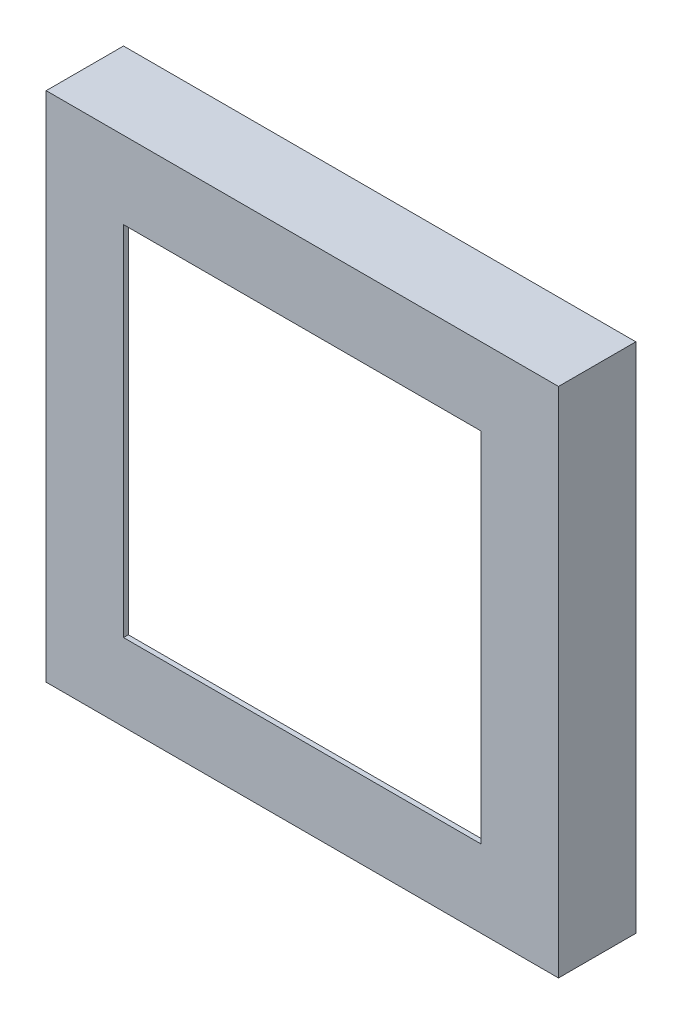
SolidWorks part; units mm, degrees
ref_plane "Front Plane" through (0, 0, 0) normal (0, 0, 1) x (1, 0, 0)
ref_plane "Top Plane" through (0, 0, 0) normal (0, 1, 0) x (1, 0, 0)
ref_plane "Right Plane" through (0, 0, 0) normal (1, 0, 0) x (0, 0, -1)
sketch "Sketch1" plane through (0, 0, 0) normal (0, 0, 1) x (1, 0, 0)
  line L0 (-1, -1) -> (-1, 105)
  line L1 (0, 0) -> (104, 0)
  line L2 (0, 0) -> (0, 104)
  line L3 (0, 104) -> (104, 104)
  line L4 (104, 0) -> (104, 104)
  line L5 (-1, 105) -> (105, 105)
  line L6 (105, -1) -> (105, 105)
  line L7 (-1, -1) -> (105, -1)
  dimension "D1" = 104
  dimension "D2" = 104
  dimension "D3" = 1
extrude "Boss-Extrude1" add sketch "Sketch1" along normal blind 15
sketch "Sketch2" plane through (0, 0, 15) normal (0, 0, 1) x (1, 0, 0)
  line L0 (-1, 105) -> (105, -1) construction
  line L1 (-1, 105) -> (105, 105)
  line L2 (-1, 105) -> (-1, -1)
  line L3 (-1, -1) -> (105, -1)
  line L4 (105, 105) -> (105, -1)
  line L5 (0, 104) -> (0, 0) construction
  line L6 (89, 15) -> (15, 15)
  line L7 (89, 15) -> (89, 89)
  line L8 (89, 89) -> (15, 89)
  line L9 (15, 15) -> (15, 89)
  line L10 (89, 15) -> (15, 89) construction
  line L11 (89, 89) -> (15, 15) construction
  point P6 (52, 52)
  dimension "D1" = 15
extrude "Boss-Extrude2" add sketch "Sketch2" along normal blind 1
